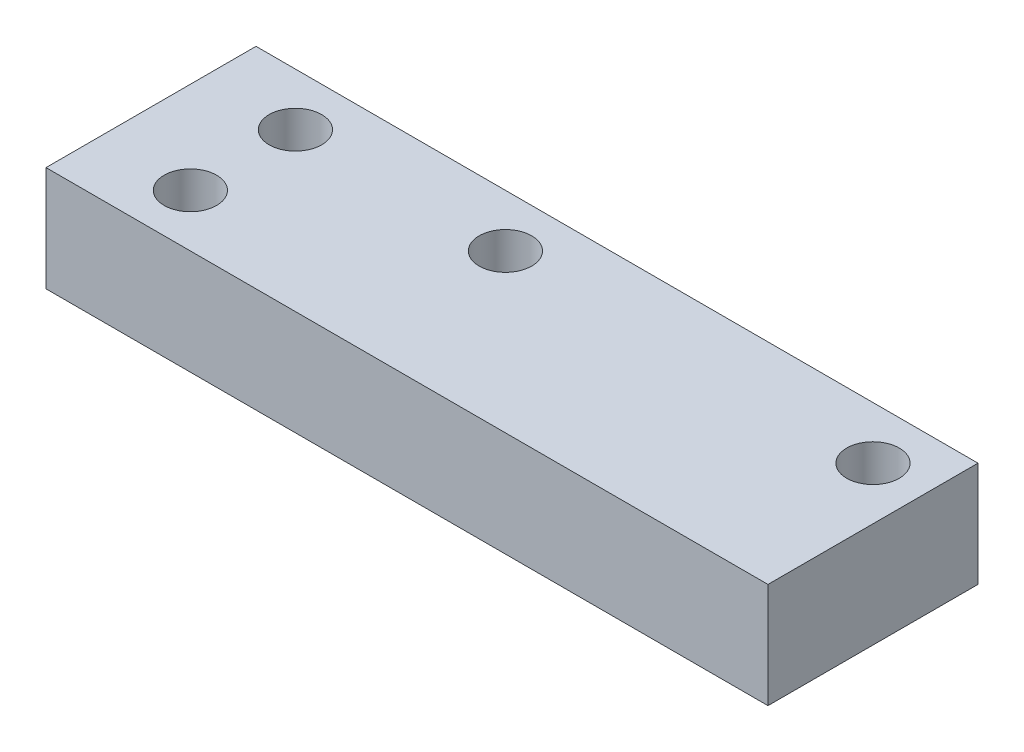
SolidWorks part; units mm, degrees
material "Oak"
ref_plane "Front Plane" through (0, 0, 0) normal (0, 0, 1) x (1, 0, 0)
ref_plane "Top Plane" through (0, 0, 0) normal (0, 1, 0) x (1, 0, 0)
ref_plane "Right Plane" through (0, 0, 0) normal (1, 0, 0) x (0, 0, -1)
sketch "Sketch2" plane through (0, 0, 0) normal (0, 1, 0) x (1, 0, 0)
  line L0 (51, 0) -> (51, -16) construction
  line L1 (0, 0) -> (55, 0)
  line L2 (0, 0) -> (0, -16)
  line L3 (0, -16) -> (55, -16)
  line L4 (55, 0) -> (55, -16)
  line L5 (23, 0) -> (23, -16) construction
  line L6 (23, -4) -> (51, -4) construction
  line L7 (51, -4) -> (55, -4) construction
  line L8 (23, -4) -> (19, -4) construction
  line L9 (19, 0) -> (19, -16) construction
  line L10 (7, 0) -> (7, -4) construction
  line L11 (0, -4) -> (7, -4) construction
  line L12 (7, -4) -> (19, -4) construction
  line L13 (7, -4) -> (7, -12) construction
  line L14 (7, -12) -> (7, -16) construction
  circle A0 centre (23, -4) radius 2
  circle A1 centre (51, -4) radius 2
  circle A2 centre (7, -4) radius 2
  circle A3 centre (7, -12) radius 2
  dimension "D5" = 4
  dimension "D6" = 4
  dimension "D8" = 4
  dimension "D9" = 4
  dimension "D1" = 55
  dimension "D2" = 16
  dimension "D3" = 36
  dimension "D4" = 28
  dimension "D7" = 4
  dimension "D10" = 12
  dimension "D11" = 8
extrude "Boss-Extrude1" add sketch "Sketch2" along normal blind 8
